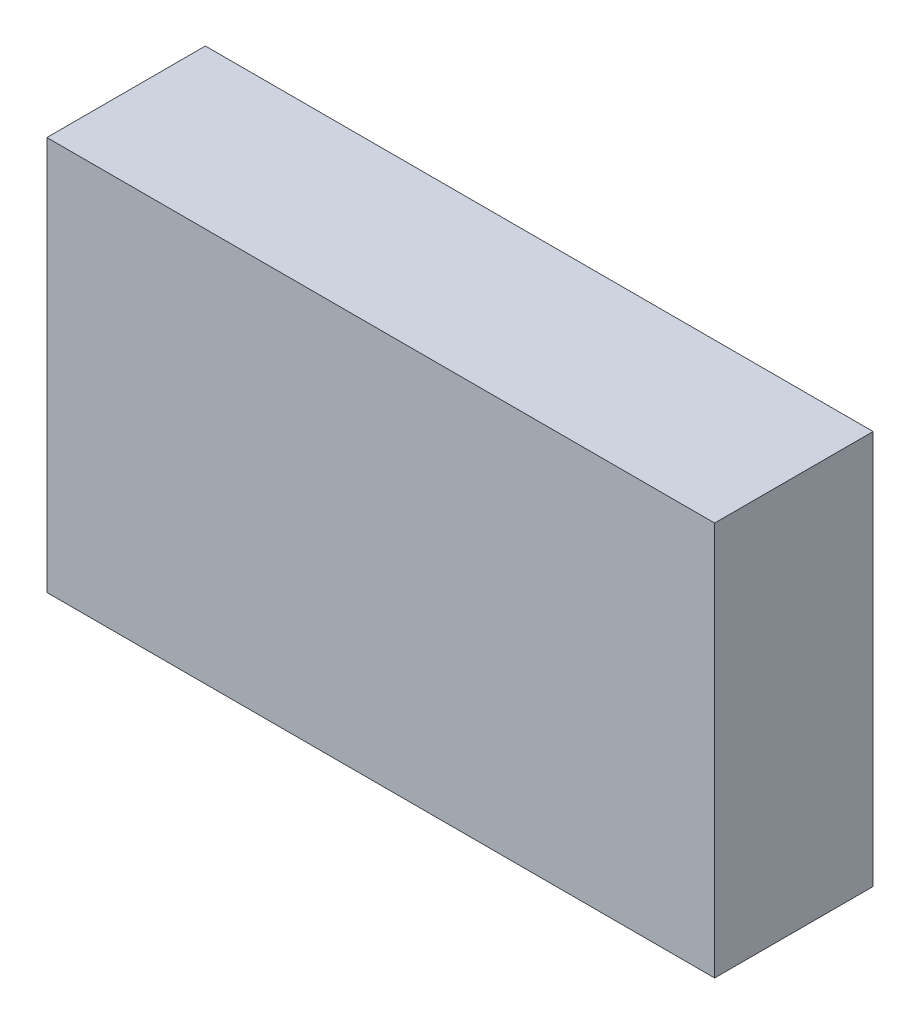
SolidWorks part; units mm, degrees
ref_plane "Front Plane" through (0, 0, 0) normal (0, 0, 1) x (1, 0, 0)
ref_plane "Top Plane" through (0, 0, 0) normal (0, 1, 0) x (1, 0, 0)
ref_plane "Right Plane" through (0, 0, 0) normal (1, 0, 0) x (0, 0, -1)
other "Configuration Table"
sketch "Sketch1" plane through (0, 0, 0) normal (0, 0, 1) x (1, 0, 0)
  line L1 (-179.4895, 82.5886) -> (111.2125, 82.5886)
  line L2 (-179.4895, 82.5886) -> (-179.4895, -88.9465)
  line L3 (-179.4895, -88.9465) -> (111.2125, -88.9465)
  line L4 (111.2125, 82.5886) -> (111.2125, -88.9465)
extrude "Boss-Extrude1" add sketch "Sketch1" along normal blind 69
